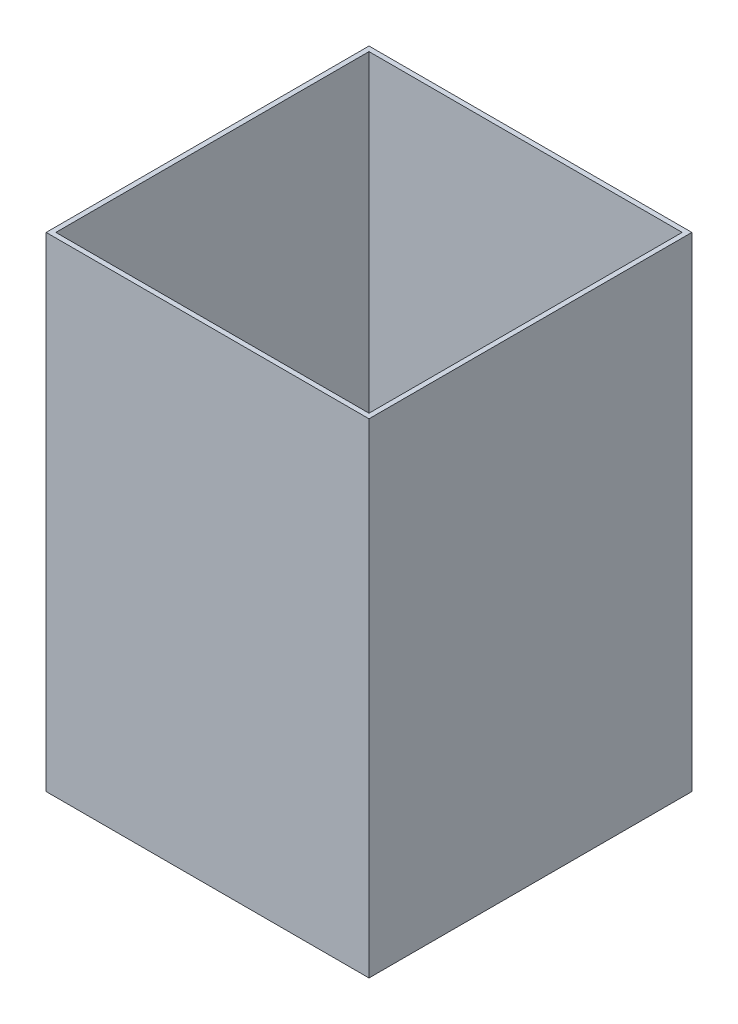
SolidWorks part; units mm, degrees
ref_plane "Front Plane" through (0, 0, 0) normal (0, 0, 1) x (1, 0, 0)
ref_plane "Top Plane" through (0, 0, 0) normal (0, 1, 0) x (1, 0, 0)
ref_plane "Right Plane" through (0, 0, 0) normal (1, 0, 0) x (0, 0, -1)
sketch "Sketch1" plane through (0, 0, 0) normal (0, 1, 0) x (1, 0, 0)
  line L1 (-50, -50) -> (50, -50)
  line L2 (-50, -50) -> (-50, 50)
  line L3 (-50, 50) -> (50, 50)
  line L4 (50, -50) -> (50, 50)
  line L5 (-50, -50) -> (50, 50) construction
  line L6 (-50, 50) -> (50, -50) construction
  line L7 (-48.5, 48.5) -> (48.5, 48.5)
  line L8 (-48.5, 48.5) -> (-48.5, -48.5)
  line L9 (-48.5, -48.5) -> (48.5, -48.5)
  line L10 (48.5, 48.5) -> (48.5, -48.5)
  line L11 (-48.5, 48.5) -> (48.5, -48.5) construction
  line L12 (-48.5, -48.5) -> (48.5, 48.5) construction
  point P0 (0, 0)
  point P6 (0, 0)
  dimension "D1" = 100
  dimension "D2" = 100
  dimension "D3" = 97
  dimension "D4" = 97
extrude "Boss-Extrude1" add sketch "Sketch1" along normal blind 150
sketch "Sketch2" plane through (50, 0, 0) normal (1, 0, 0) x (0, 0, -1)
  line L0 (0, -1000) -> (0, 49000) construction
  line L1 (-50, 0) -> (50, 0) construction
  line L2 (-950, 75) -> (49050, 75) construction
  line L3 (50, 150) -> (50, 0) construction
  circle A0 centre (0, 75) radius 3.5428
  point P5 (0, 0)
  point P10 (50, 75)
